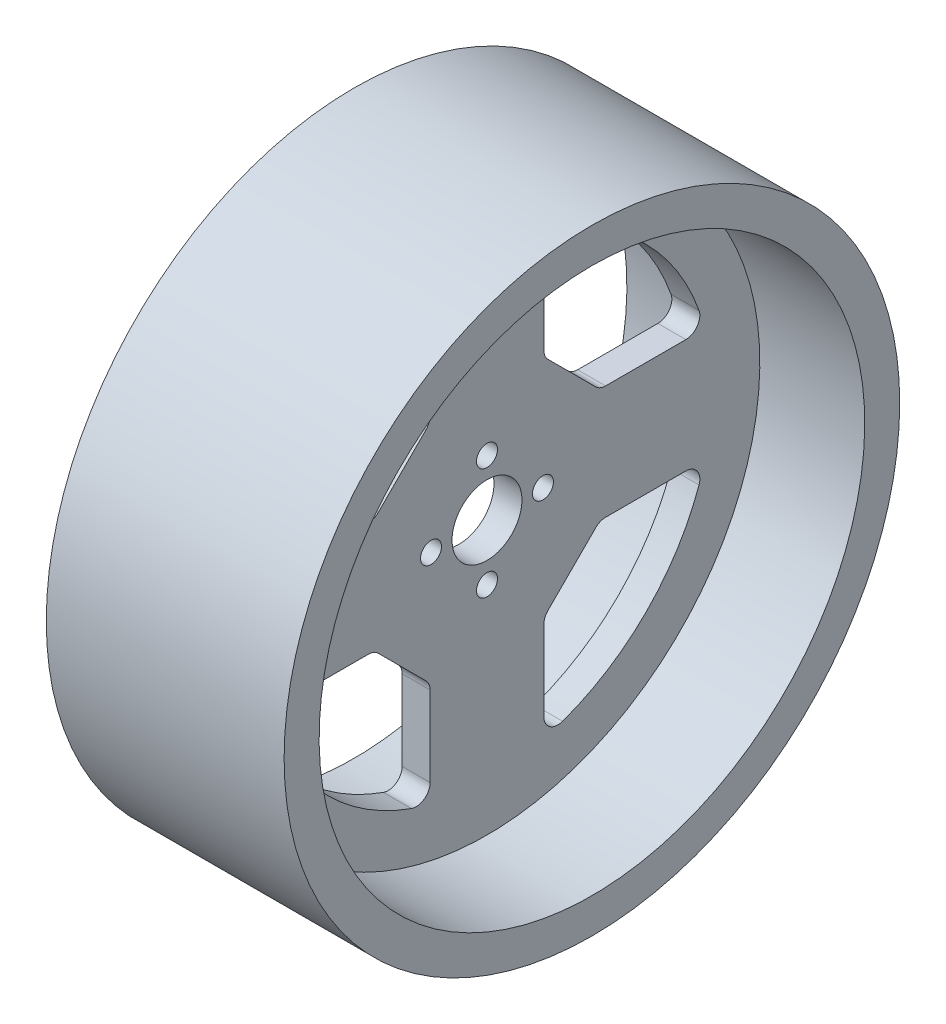
SolidWorks part; units mm, degrees
ref_plane "Front Plane" through (0, 0, 0) normal (0, 0, 1) x (1, 0, 0)
ref_plane "Top Plane" through (0, 0, 0) normal (0, 1, 0) x (1, 0, 0)
ref_plane "Right Plane" through (0, 0, 0) normal (1, 0, 0) x (0, 0, -1)
sketch "Sketch1" plane through (0, 0, 0) normal (0, 0, 1) x (1, 0, 0)
  line L0 (2, 0) -> (2, 39)
  line L1 (2, 39) -> (17, 39)
  line L2 (17, 39) -> (17, 44)
  line L3 (2, 0) -> (0, 0)
  line L4 (0, 0) -> (0, 44)
  line L5 (0, 44) -> (17, 44)
  dimension "D1" = 44
  dimension "D2" = 5
  dimension "D3" = 2
  dimension "D4" = 17
revolve "Revolve1" add sketch "Sketch1" angle 360 about L3
mirror "Mirror1" about plane through (0, 0, 0) normal (-1, 0, 0) of "Revolve1"
sketch "Sketch2" plane through (2, 0, 0) normal (1, 0, 0) x (0, 0, -1)
  circle A0 centre (0, 0) radius 5
  circle A1 centre (8, 0) radius 1.5
  circle A2 centre (0, -8) radius 1.5
  circle A3 centre (-8, 0) radius 1.5
  circle A4 centre (0, 8) radius 1.5
  dimension "D1" = 10
  dimension "D2" = 3
  dimension "D3" = 8
  dimension "D4" = 4
extrude "holes" cut sketch "Sketch2" against normal up to surface (4 mm away) up to face at (-2, 39, 0)
sketch "Sketch3" plane through (2, 0, 0) normal (1, 0, 0) x (0, 0, -1)
  line L0 (0, 0) -> (0, 39) construction
  line L1 (1.0607, 9.0607) -> (9.0607, 1.0607) construction
  line L2 (-8, 0) -> (0, 8) construction
  line L3 (0, -8) -> (8, 0) construction
  line L4 (8.1317, 16.1317) -> (16.1317, 8.1317)
  line L5 (8.1317, 31.1317) -> (8.1317, 16.1317)
  line L6 (16.1317, 8.1317) -> (31.1317, 8.1317)
  line L7 (16.1317, 8.1317) -> (8.1317, 8.1317) construction
  line L8 (8.1317, 8.1317) -> (8.1317, 16.1317) construction
  line L9 (0, 0) -> (39, 0) construction
  circle A0 centre (0, 0) radius 39 construction
  circle A2 centre (0, 8) radius 1.5 construction
  circle A3 centre (8, 0) radius 1.5 construction
  arc A5 (31.1317, 8.1317) -> (8.1317, 31.1317) centre (0, 0) ccw
  dimension "D2" = 10
  dimension "D3" = 15
extrude "spokes" cut sketch "Sketch3" against normal up to surface (4 mm away) up to face at (-2, -1.5, -8)
fillet "Fillet2" radius 2 4 edges at (0, 8.1317, -16.1317) (0, 16.1317, -8.1317) (0, 31.1317, -8.1317) (0, 8.1317, -31.1317)
pattern_circular "CirPattern2" count 4 over 360 about axis through (0, 0, 0) along (1, 0, 0) of "spokes", "Fillet2"
